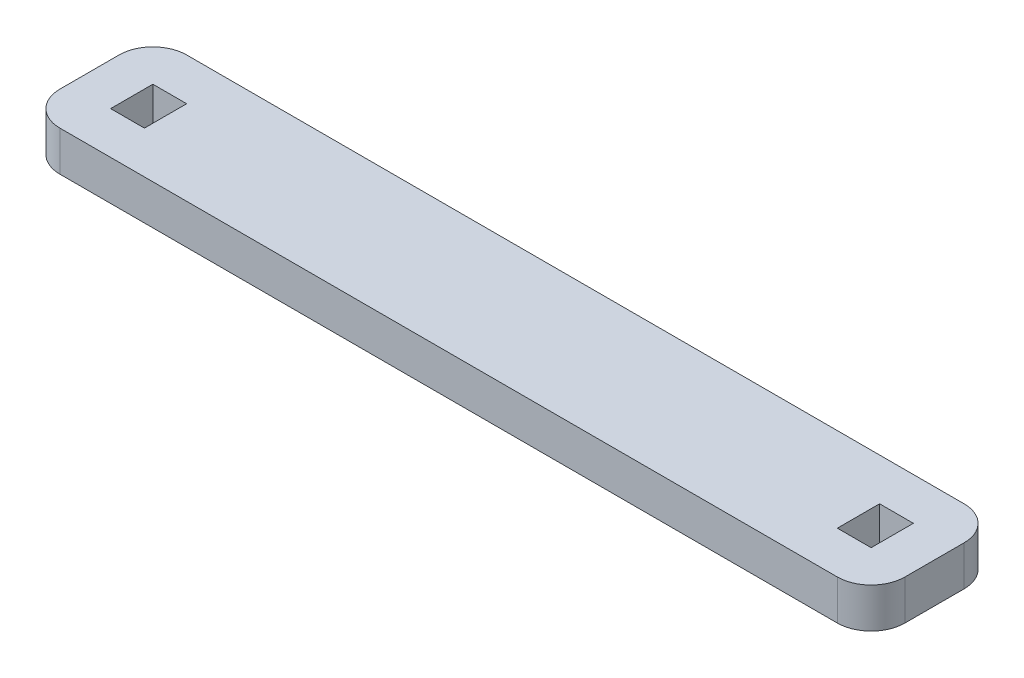
SolidWorks part; units mm, degrees
ref_plane "Front Plane" through (0, 0, 0) normal (0, 0, 1) x (1, 0, 0)
ref_plane "Top Plane" through (0, 0, 0) normal (0, 1, 0) x (1, 0, 0)
ref_plane "Right Plane" through (0, 0, 0) normal (1, 0, 0) x (0, 0, -1)
sketch "Sketch1" plane through (0, 0, 0) normal (0, 1, 0) x (1, 0, 0)
  line L0 (-27.305, 0) -> (27.305, 0) construction
  line L6 (31.75, -4.7625) -> (-31.75, -4.7625)
  line L7 (-26.035, -1.5875) -> (-28.575, -1.5875)
  line L8 (-26.035, -1.5875) -> (-26.035, 1.5875)
  line L9 (-26.035, 1.5875) -> (-28.575, 1.5875)
  line L10 (-28.575, -1.5875) -> (-28.575, 1.5875)
  line L11 (-26.035, -1.5875) -> (-28.575, 1.5875) construction
  line L12 (-26.035, 1.5875) -> (-28.575, -1.5875) construction
  line L13 (28.575, -1.5875) -> (26.035, -1.5875)
  line L14 (28.575, -1.5875) -> (28.575, 1.5875)
  line L15 (28.575, 1.5875) -> (26.035, 1.5875)
  line L16 (26.035, -1.5875) -> (26.035, 1.5875)
  line L17 (28.575, -1.5875) -> (26.035, 1.5875) construction
  line L18 (28.575, 1.5875) -> (26.035, -1.5875) construction
  line L19 (31.75, -4.7625) -> (31.75, 4.7625)
  line L20 (31.75, 4.7625) -> (-31.75, 4.7625)
  line L21 (-31.75, -4.7625) -> (-31.75, 4.7625)
  line L22 (31.75, -4.7625) -> (-31.75, 4.7625) construction
  line L23 (31.75, 4.7625) -> (-31.75, -4.7625) construction
  point P0 (0, 0)
  point P1 (0, 0)
  point P6 (-27.305, 0)
  point P11 (27.305, 0)
  dimension "D1" = 9.525
  dimension "D2" = 3.175
  dimension "D3" = 2.54
  dimension "D4" = 54.61
  dimension "D5" = 3.175
extrude "Boss-Extrude1" add sketch "Sketch1" along normal mid plane 3
fillet "Fillet1" radius 2.54 4 edges at (-31.75, 0, -4.7625) (31.75, 0, -4.7625) (31.75, 0, 4.7625) (-31.75, 0, 4.7625)
